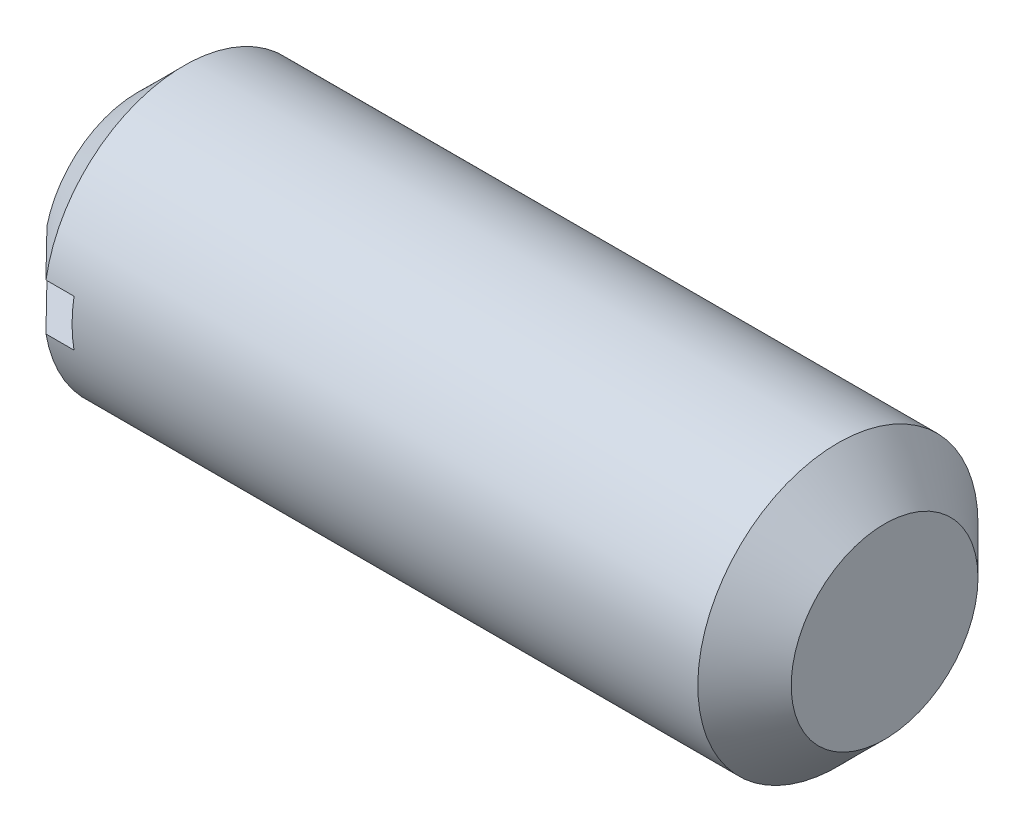
SolidWorks part; units mm, degrees
material "Нержавеющая сталь типа AISI 316L"
ref_plane "Спереди" through (0, 0, 0) normal (0, 0, 1) x (1, 0, 0)
ref_plane "Сверху" through (0, 0, 0) normal (0, 1, 0) x (1, 0, 0)
ref_plane "Справа" through (0, 0, 0) normal (1, 0, 0) x (0, 0, -1)
sketch "Эскиз1" plane through (0, 0, 0) normal (1, 0, 0) x (0, 0, -1)
  circle A0 centre (0, 0) radius 3
  dimension "D1" = 6
extrude "Бобышка-Вытянуть1" add sketch "Эскиз1" along normal blind 16
cosmetic thread "Условное изображение резьбы1" parameters "D2"=4.891
cosmetic thread "Условное изображение резьбы2" [suppressed] parameters "D2"=4.11
sketch "Эскиз2" plane through (0, 0, 0) normal (0, 0, 1) x (1, 0, 0)
  line L1 (0, -0.5) -> (1.6, -0.5)
  line L2 (0, -0.5) -> (0, 0.5)
  line L3 (0, 0.5) -> (1.6, 0.5)
  line L4 (1.6, -0.5) -> (1.6, 0.5)
  point P4 (0, 0)
  dimension "D1" = 1.6
  dimension "D2" = 1
extrude "Вырез-Вытянуть1" cut sketch "Эскиз2" against normal through all and the other way through all
chamfer "Фаска1" distance 1 angle 45 3 edges at (16, 0, -3) (0, 3, 0) (0, -3, 0)
